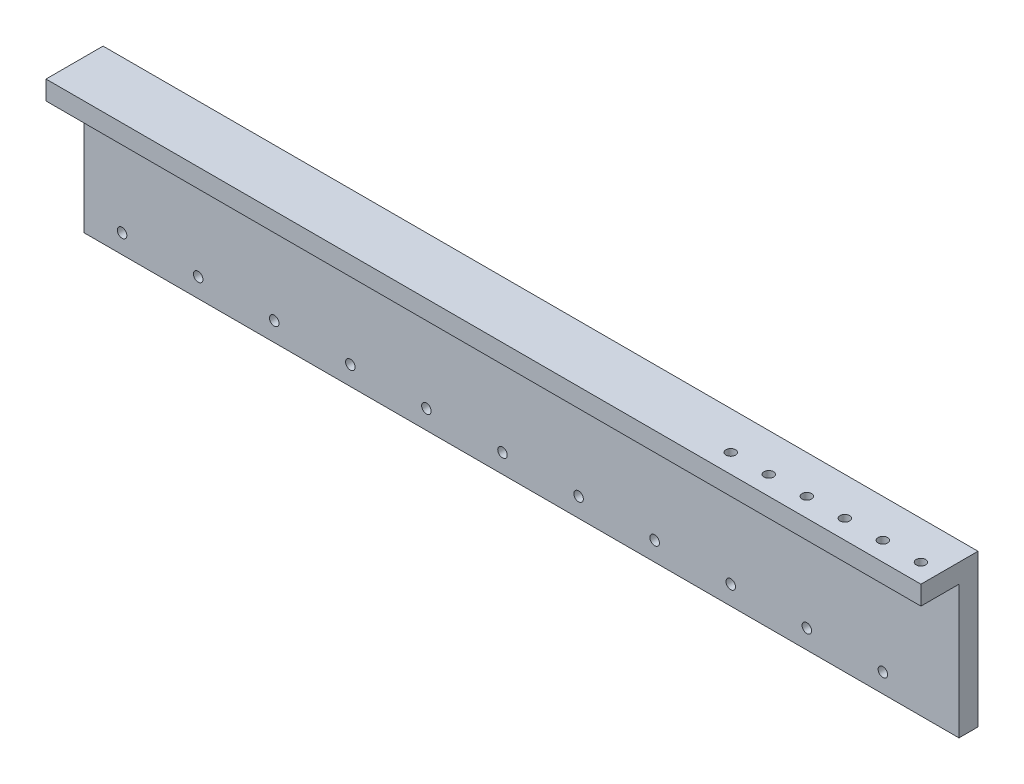
SolidWorks part; units mm, degrees
ref_plane "Front Plane" through (0, 0, 0) normal (0, 0, 1) x (1, 0, 0)
ref_plane "Top Plane" through (0, 0, 0) normal (0, 1, 0) x (1, 0, 0)
ref_plane "Right Plane" through (0, 0, 0) normal (1, 0, 0) x (0, 0, -1)
sketch "Sketch1" plane through (0, 0, 0) normal (0, 0, 1) x (1, 0, 0)
  line L1 (-115, -20) -> (115, -20)
  line L2 (-115, -20) -> (-115, 20)
  line L3 (-115, 20) -> (115, 20)
  line L4 (115, -20) -> (115, 20)
  line L5 (-115, -20) -> (115, 20) construction
  line L6 (-115, 20) -> (115, -20) construction
  circle A0 centre (-105, -15) radius 1.25
  circle A1 centre (-85, -15) radius 1.25
  circle A2 centre (-65, -15) radius 1.25
  circle A3 centre (-45, -15) radius 1.25
  circle A4 centre (-25, -15) radius 1.25
  circle A5 centre (-5, -15) radius 1.25
  circle A6 centre (15, -15) radius 1.25
  circle A7 centre (35, -15) radius 1.25
  circle A8 centre (55, -15) radius 1.25
  circle A9 centre (75, -15) radius 1.25
  circle A10 centre (95, -15) radius 1.25
  point P0 (0, 0)
  dimension "D3" = 10
  dimension "D1" = 40
  dimension "D2" = 230
  dimension "D4" = 5
  dimension "D5" = 11
extrude "Boss-Extrude1" add sketch "Sketch1" along normal blind 5
sketch "Sketch2" plane through (0, 0, 5) normal (0, 0, 1) x (1, 0, 0)
  line L0 (115, -20) -> (115, 20) construction
  line L1 (-115, 20) -> (115, 20)
  line L2 (-115, 20) -> (-115, 15)
  line L3 (-115, 15) -> (115, 15)
  line L4 (115, 20) -> (115, 15)
  dimension "D1" = 5
extrude "Boss-Extrude2" add sketch "Sketch2" along normal blind 10
sketch "Sketch3" plane through (0, 20, 0) normal (0, 1, 0) x (1, 0, 0)
  line L0 (115, -15) -> (115, 0) construction
  line L1 (115, -15) -> (-115, -15) construction
  circle A0 centre (110, -10) radius 1.25
  circle A1 centre (100, -10) radius 1.25
  circle A2 centre (90, -10) radius 1.25
  circle A3 centre (80, -10) radius 1.25
  circle A4 centre (70, -10) radius 1.25
  circle A5 centre (60, -10) radius 1.25
  dimension "D1" = 5
  dimension "D2" = 5
  dimension "D3" = 6
extrude "Cut-Extrude1" cut sketch "Sketch3" against normal up to next
